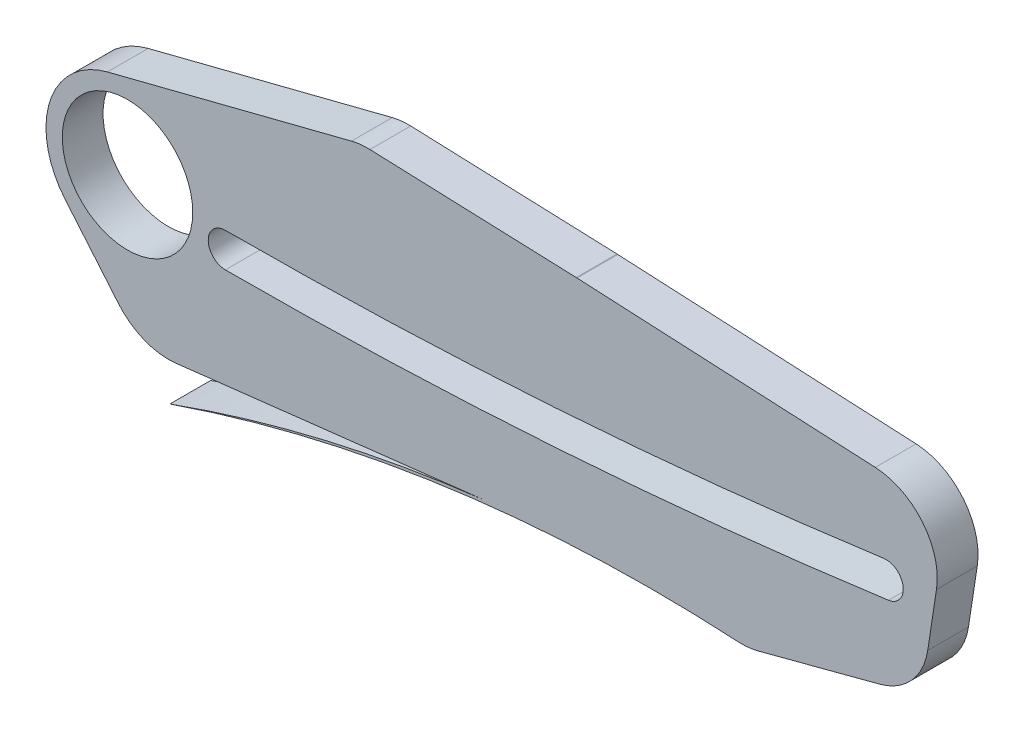
SolidWorks part; units mm, degrees
material "Thornel Mat VMA"
ref_plane "前视基准面" through (0, 0, 0) normal (0, 0, 1) x (1, 0, 0)
ref_plane "上视基准面" through (0, 0, 0) normal (0, 1, 0) x (1, 0, 0)
ref_plane "右视基准面" through (0, 0, 0) normal (1, 0, 0) x (0, 0, -1)
sketch "草图1" plane through (0, 0, 0) normal (0, 0, 1) x (1, 0, 0)
  line L0 (-1.2337, 4.8454) -> (14.2923, 8.7985)
  line L1 (50.2857, 7.1689) -> (48.9717, -1.3872)
  line L2 (48.9717, -1.3872) -> (38.1143, -2.7242)
  line L3 (38.1143, -2.7242) -> (18.3845, -4.7903)
  line L4 (-2.3728, -4.4011) -> (3.1242, -7.3648)
  line L5 (3.1242, -7.3648) -> (18.3845, -4.7903)
  line L6 (0, 0) -> (3.1242, -7.3648) construction
  line L7 (14.2923, 8.7985) -> (27.5418, 8.3025)
  line L8 (27.5418, 8.3025) -> (50.2857, 7.1689)
  circle A0 centre (0, 0) radius 4
  arc A1 (-1.2337, 4.8454) -> (-2.3728, -4.4011) centre (0, 0) ccw
  dimension "D1" = 8
  dimension "D3" = 8
extrude "凸台-拉伸1" add sketch "草图1" along normal mid plane 2.5
sketch "草图2" plane through (0, 0, 1.25) normal (0, 0, 1) x (1, 0, 0)
  line L0 (0, 0) -> (0, -1) construction
  line L1 (0, -1) -> (6, -1) construction
  arc A0 (6, -1) -> (46.5237, 1.777) centre (6, 296.0619) ccw construction
  arc A1 (6, -2.05) -> (46.6669, 0.7368) centre (6, 296.0619) ccw
  arc A2 (6, 0.05) -> (46.3805, 2.8172) centre (6, 296.0619) ccw
  arc A3 (6, 0.05) -> (6, -2.05) centre (6, -1) ccw
  arc A4 (46.6669, 0.7368) -> (46.3805, 2.8172) centre (46.5237, 1.777) ccw
  point P3 (26.3094, -0.3049)
  dimension "D2" = 1.05
  dimension "D1" = 1
  dimension "D3" = 6
extrude "切除-拉伸1" cut sketch "草图2" against normal blind 22
sketch "草图3" plane through (0, 0, -1.25) normal (0, 0, -1) x (-1, 0, 0)
  line L0 (3.8302, -3.2139) -> (-2.5977, -10.8744)
  line L1 (-48.9717, -1.3872) -> (-50.2857, 7.1689) construction
  line L2 (-48.9717, -1.3872) -> (-48.061, -7.3177)
  line L3 (0, 0) -> (8.4103, 0) construction
  line L4 (2.3728, -4.4011) -> (-3.1242, -7.3648) construction
  line L5 (-3.1242, -7.3648) -> (-18.3845, -4.7903) construction
  line L6 (-18.3845, -4.7903) -> (-38.1143, -2.7242) construction
  line L7 (-38.1143, -2.7242) -> (-48.9717, -1.3872) construction
  line L8 (2.3728, -4.4011) -> (-3.1242, -7.3648)
  line L9 (-3.1242, -7.3648) -> (-18.3845, -4.7903)
  line L10 (-18.3845, -4.7903) -> (-38.1143, -2.7242)
  line L11 (-38.1143, -2.7242) -> (-48.9717, -1.3872)
  arc A0 (2.3728, -4.4011) -> (3.8302, -3.2139) centre (0, 0) ccw
  arc A1 (-2.5977, -10.8744) -> (-48.061, -7.3177) centre (-32.204, -96.9712) ccw
  arc A2 (-21.1325, -64.2993) -> (-15.2042, -105.7918) centre (-14.9925, -84.5918) ccw construction
  dimension "D1" = 10
  dimension "D2" = 50
  dimension "D3" = 10
  dimension "D4" = 6
extrude "凸台-拉伸2" add sketch "草图3" against normal blind 2.5
sketch "草图4" plane through (0, 0, -1.25) normal (0, 0, -1) x (-1, 0, 0)
  line L0 (-48.6753, -3.3177) -> (-38.061, -6.1148)
  line L1 (-48.061, -7.3177) -> (-50.2857, 7.1689) construction
  line L2 (-48.6753, -3.3177) -> (-48.061, -7.3177)
  arc A0 (-2.5977, -10.8744) -> (-48.061, -7.3177) centre (-32.204, -96.9712) ccw construction
  arc A1 (-38.061, -6.1148) -> (-48.061, -7.3177) centre (-32.204, -96.9712) ccw
  dimension "D1" = 4
  dimension "D2" = 10
extrude "切除-拉伸2" cut sketch "草图4" against normal blind 2.5
sketch "草图6" plane through (0, 0, -1.25) normal (0, 0, -1) x (-1, 0, 0)
  line L2 (-21.4799, -27.5865) -> (-57.3508, -49.4334)
  line L3 (-31.7892, -91.6698) -> (-18.1445, -6.8531)
  line L4 (-31.7892, -91.6698) -> (-21.9166, -6.3318)
  line L5 (-21.9166, -6.3318) -> (-0.8327, -8.771)
  line L6 (-2.5977, -10.8744) -> (3.8302, -3.2139) construction
  line L7 (-0.8327, -8.771) -> (-2.5977, -10.8744)
  circle A2 centre (-3.3342, -43.2942) radius 3
  circle A4 centre (-12.8889, -82.0644) radius 55.1511
  circle A6 centre (-5.0298, -186.9213) radius 50
  circle A8 centre (-21.4799, -27.5865) radius 21 construction
  circle A10 centre (-12.8889, -82.0644) radius 77.1011
  circle A12 centre (-12.8889, -82.0644) radius 33.2011
  circle A14 centre (-31.7892, -91.6698) radius 85.9072
  circle A16 centre (-57.3508, -49.4334) radius 21
  arc A17 (-40.5222, 2.6433) -> (-6.2294, -170.9162) centre (-12.8889, -82.0644) ccw
  circle A19 centre (-24.4391, -28.1363) radius 21.95
  arc M17 (-38.061, -6.1148) -> (-2.5977, -10.8744) centre (-32.204, -96.9712) cw
  line M18 (-2.5977, -10.8744) -> (3.8302, -3.2139)
extrude "切除-拉伸4" cut sketch "草图6" against normal blind 10 contours L5 M17 M18
fillet "圆角1" radius 4 6 edges at (14.2923, 8.7985, 0) (27.5418, 8.3025, 0) (50.2857, 7.1689, 0) (38.061, -6.1148, 0) (48.6753, -3.3177, 0) (0.8327, -8.771, 0)
